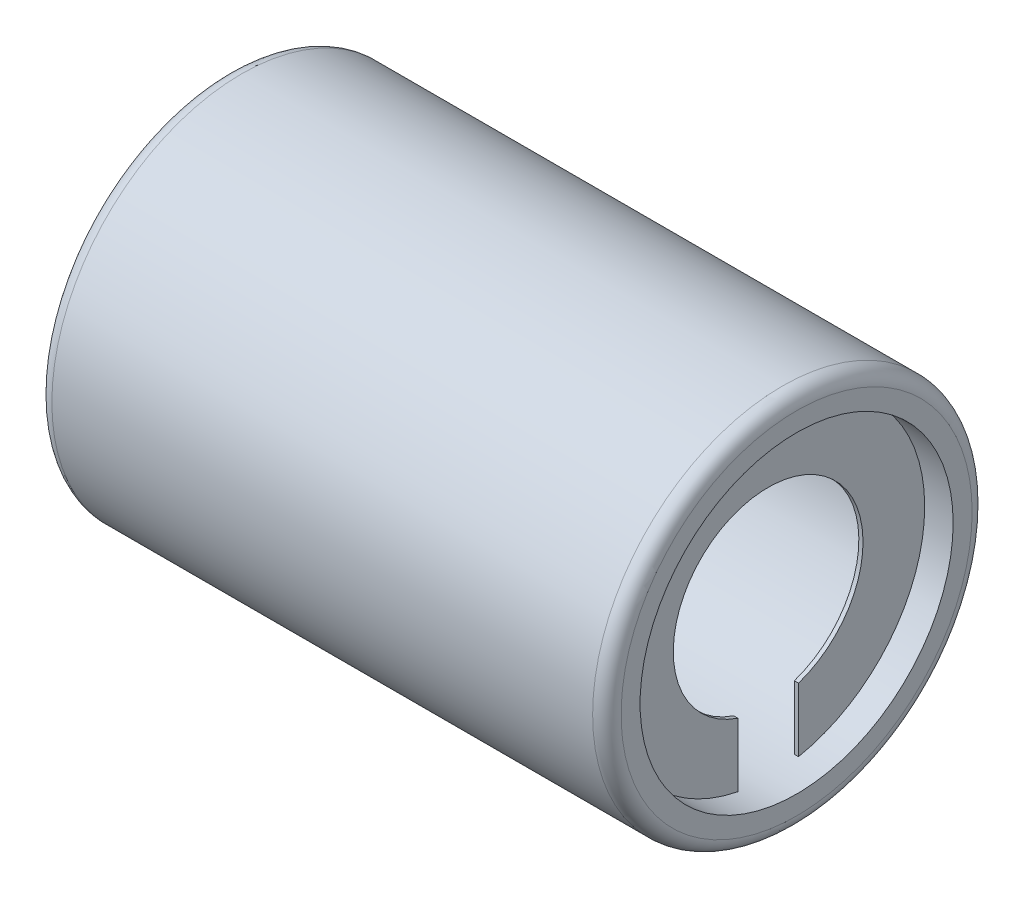
SolidWorks part; units mm, degrees
ref_plane "Front Plane" through (0, 0, 0) normal (0, 0, 1) x (1, 0, 0)
ref_plane "Top Plane" through (0, 0, 0) normal (0, 1, 0) x (1, 0, 0)
ref_plane "Right Plane" through (0, 0, 0) normal (1, 0, 0) x (0, 0, -1)
ref_plane "Plane1" through (0, 0, 0) normal (0, 0, -1) x (-1, 0, 0)
sketch "Sketch1" plane through (0, 0, 0) normal (0, 0, -1) x (-1, 0, 0)
  line L0 (-12, 4) -> (-12, 0)
  line L1 (-12, 0) -> (0, 0)
  line L2 (0, 0) -> (0, 4)
  line L3 (0, 4) -> (-12, 4)
  line L4 (-12, 0) -> (0, 0) construction
revolve "Revolve1" add sketch "Sketch1" angle 360 about L4
hole_wizard "Ø6.6 (6.6) Diameter Hole1" positions "Sketch3" profile "Sketch2" hole size "Ø6.6" standard "ANSI Metric"
sketch "Sketch3" plane through (12, 0, 0) normal (1, 0, 0) x (0, 0, -1)
  point P0 (0, 0)
sketch "Sketch2" plane through (12, 0, 0) normal (0, 1, 0) x (0, 0, -1)
  line L0 (0, 0) -> (0, 12)
  line L1 (0, 12) -> (3.3, 12)
  line L2 (3.3, 12) -> (3.3, 0)
  line L5 (3.3, 0) -> (0, 0)
  line L11 (0, -6.35) -> (0, 107.95) construction
  dimension "Thru Hole Dia." = 6.6
  dimension "Thru Hole Depth" = 12
ref_plane "Plane2" through (11.312, 0, 0) normal (-1, 0, 0) x (0, -1, 0)
sketch "Sketch4" plane through (11.312, 0, 0) normal (-1, 0, 0) x (0, -1, 0)
  line L0 (1.8948, 0.64) -> (3.2373, 0.64)
  line L1 (3.2373, -0.64) -> (1.8948, -0.64)
  arc A0 (3.2373, 0.64) -> (3.2373, -0.64) centre (0, 0) ccw
  arc A1 (1.8948, -0.64) -> (1.8948, 0.64) centre (0, 0) ccw
extrude "Boss-Extrude1" add sketch "Sketch4" against normal blind 0.088
sketch "Sketch5" plane through (0, 0, 0) normal (0, 0, -1) x (-1, 0, 0)
  line L0 (-11.4, 2) -> (-11.4, 0)
  line L1 (-11.4, 0) -> (0, 0)
  line L2 (0, 0) -> (0, 3.3)
  line L3 (0, 3.3) -> (-0.6, 3.3)
  line L4 (-0.6, 3.3) -> (-0.6, 2)
  line L5 (-0.6, 2) -> (-11.4, 2)
  line L6 (-11.4, 0) -> (0, 0) construction
revolve "Cut-Revolve1" cut sketch "Sketch5" angle 360 about L6
fillet "Fillet1" radius 0.3 2 edges at (0, 0, 4) (12, 0, 4)
